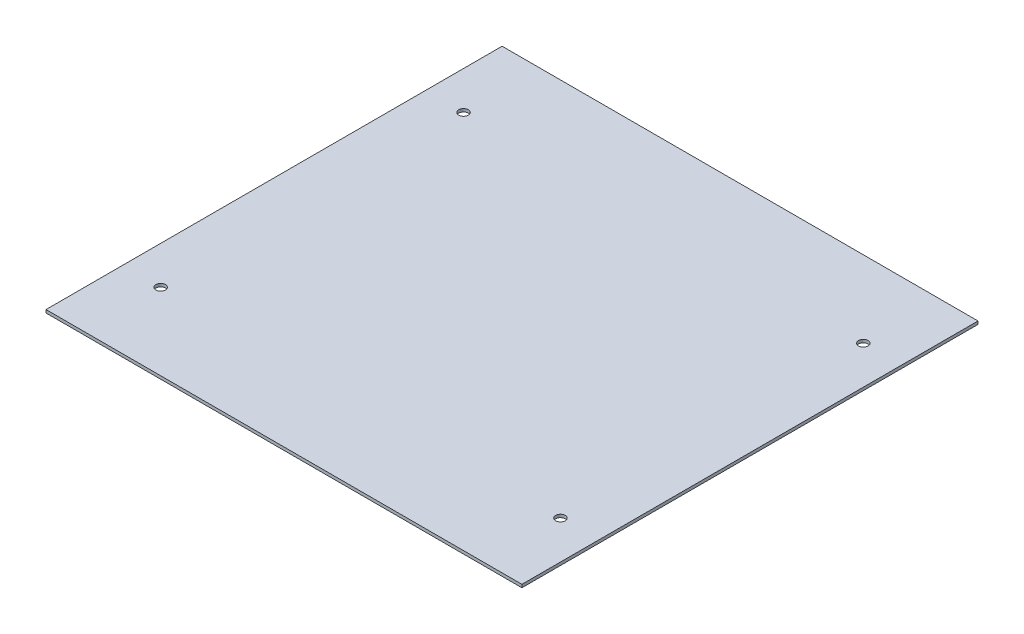
SolidWorks part; units mm, degrees
material "5052-H32"
ref_plane "Front Plane" through (0, 0, 0) normal (0, 0, 1) x (1, 0, 0)
ref_plane "Top Plane" through (0, 0, 0) normal (0, 1, 0) x (1, 0, 0)
ref_plane "Right Plane" through (0, 0, 0) normal (1, 0, 0) x (0, 0, -1)
sketch "Sketch1" plane through (0, 0, 0) normal (0, 1, 0) x (1, 0, 0)
  line L1 (-250, -239.6) -> (250, -239.6)
  line L2 (-250, -239.6) -> (-250, 239.6)
  line L3 (-250, 239.6) -> (250, 239.6)
  line L4 (250, -239.6) -> (250, 239.6)
  line L5 (-250, -239.6) -> (250, 239.6) construction
  line L6 (-250, 239.6) -> (250, -239.6) construction
  point P0 (0, 0)
  dimension "D1" = 479.2
  dimension "D2" = 500
extrude "Boss-Extrude1" add sketch "Sketch1" along normal blind 3.175
sketch "Sketch2" plane through (0, 3.175, 0) normal (0, 1, 0) x (1, 0, 0)
  line L0 (-250, 239.6) -> (-250, -239.6) construction
  line L1 (-250, -239.6) -> (250, -239.6) construction
  line L2 (250, 239.6) -> (-250, 239.6) construction
  line L3 (250, -239.6) -> (250, 239.6) construction
  line L4 (210, -159.1) -> (-210, -159.1) construction
  line L5 (-210, -159.1) -> (-210, 159.1) construction
  line L6 (-210, 159.1) -> (210, 159.1) construction
  line L7 (210, 159.1) -> (210, -159.1) construction
  circle A0 centre (-210, 159.1) radius 5
  circle A1 centre (210, 159.1) radius 5
  circle A2 centre (-210, -159.1) radius 5
  circle A3 centre (210, -159.1) radius 5
  dimension "D1" = 10
  dimension "D2" = 40
  dimension "D3" = 80.5
  dimension "D4" = 80.5
  dimension "D7" = 40
extrude "Cut-Extrude1" cut sketch "Sketch2" against normal up to next
